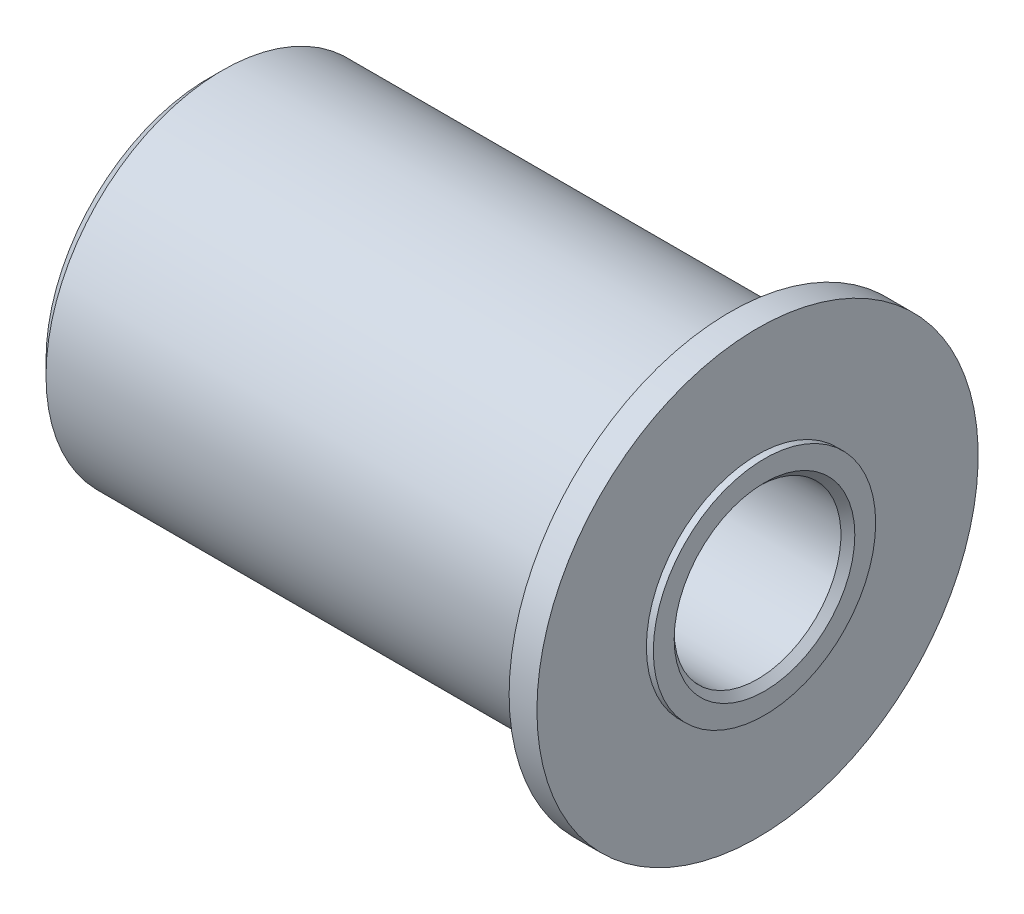
SolidWorks part; units mm, degrees
material "AISI 1010 Barra de acero laminada en caliente"
ref_plane "Alzado" through (0, 0, 0) normal (0, 0, 1) x (1, 0, 0)
ref_plane "Planta" through (0, 0, 0) normal (0, 1, 0) x (1, 0, 0)
ref_plane "Vista lateral" through (0, 0, 0) normal (1, 0, 0) x (0, 0, -1)
sketch "Croquis1" plane through (0, 0, 0) normal (0, 0, 1) x (1, 0, 0)
  line L0 (0, 0) -> (40, 0) construction
  line L1 (1, 12.7) -> (37.5, 12.7)
  line L8 (1, 6) -> (39.5, 6)
  line L10 (0, 11.7) -> (0, 7)
  line L12 (40, 8) -> (40, 6.5)
  line L13 (39.5, 15.875) -> (39.5, 8)
  line L14 (39.5, 8) -> (40, 8)
  line L15 (0, 11.7) -> (1, 12.7)
  line L17 (0, 7) -> (1, 6)
  line L18 (39.5, 6) -> (40, 6.5)
  line L19 (39.5, 15.875) -> (37.5, 15.875)
  line L20 (37.5, 15.875) -> (37.5, 12.7)
  point P3 (0, 12.7)
  point P6 (0, 6)
  point P11 (40, 6)
  dimension "D1" = 40
  dimension "D2" = 6
  dimension "D3" = 12.7
  dimension "D4" = 8
  dimension "D5" = 0.5
  dimension "D6" = 15.875
  dimension "D7" = 2
revolve "Revolución1" add sketch "Croquis1" angle 360 about L0
